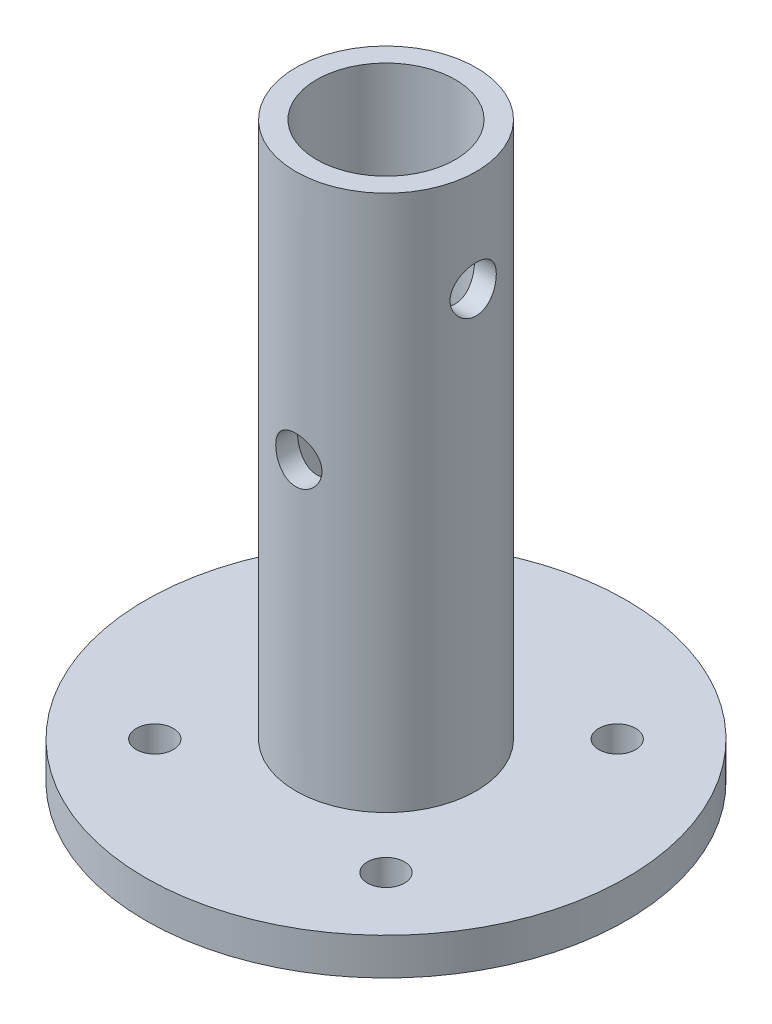
SolidWorks part; units mm, degrees
ref_plane "Front Plane" through (0, 0, 0) normal (0, 0, 1) x (1, 0, 0)
ref_plane "Top Plane" through (0, 0, 0) normal (0, 1, 0) x (1, 0, 0)
ref_plane "Right Plane" through (0, 0, 0) normal (1, 0, 0) x (0, 0, -1)
sketch "Sketch1" plane through (0, 0, 0) normal (0, 1, 0) x (1, 0, 0)
  line L1 (-12.5, 12.5) -> (12.5, 12.5) construction
  line L2 (-12.5, 12.5) -> (-12.5, -12.5) construction
  line L3 (-12.5, -12.5) -> (12.5, -12.5) construction
  line L4 (12.5, 12.5) -> (12.5, -12.5) construction
  line L5 (-12.5, 12.5) -> (12.5, -12.5) construction
  line L6 (-12.5, -12.5) -> (12.5, 12.5) construction
  circle A0 centre (0, 0) radius 26
  circle A3 centre (-12.5, 12.5) radius 2
  circle A4 centre (-12.5, -12.5) radius 2
  circle A5 centre (12.5, 12.5) radius 2
  circle A6 centre (12.5, -12.5) radius 2
  circle A7 centre (0, 0) radius 7.5
  dimension "D1" = 25
  dimension "D3" = 15
  dimension "D2" = 25
extrude "Boss-Extrude1" add sketch "Sketch1" along normal blind 4
sketch "Sketch3" plane through (0, 4, 0) normal (0, 1, 0) x (1, 0, 0)
  circle A0 centre (0, 0) radius 9.75
  circle A3 centre (0, 0) radius 7.5
  dimension "D1" = 19.5
  dimension "D2" = 15
extrude "Boss-Extrude2" add sketch "Sketch3" along normal blind 58
sketch "Sketch5" plane through (0, 0, 0) normal (0, 0, 1) x (1, 0, 0)
  line L0 (0, 43) -> (-9.75, 43) construction
  line L2 (0, 27) -> (-9.75, 27) construction
  line L3 (-9.75, 62) -> (-9.75, 4) construction
  line L4 (0, 43) -> (0, 27) construction
  circle A0 centre (0, 35) radius 2.5
extrude "Cut-Extrude1" cut sketch "Sketch5" against normal through all and the other way through all
sketch "Sketch6" plane through (0, 0, 0) normal (1, 0, 0) x (0, 0, -1)
  line L0 (0, 62) -> (0, 40) construction
  line L1 (7.5, 62) -> (-7.5, 62) construction
  line L2 (0, 40) -> (7.4339, 40) construction
  circle A0 centre (0, 51) radius 2.5
extrude "Cut-Extrude2" cut sketch "Sketch6" against normal through all and the other way through all
